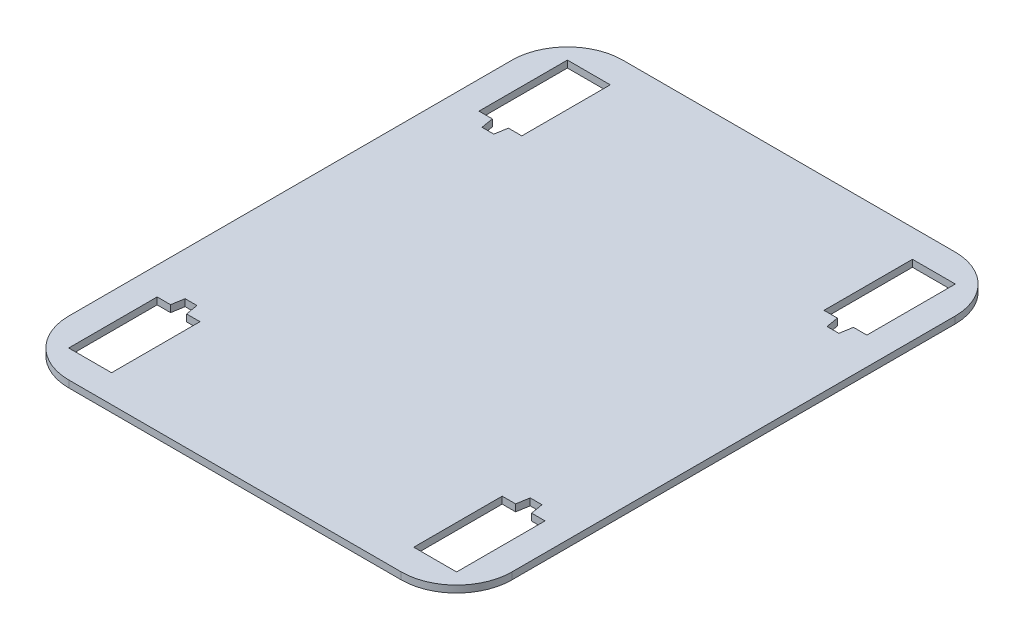
SolidWorks part; units mm, degrees
material "Plain Carbon Steel"
ref_plane "Front" through (0, 0, 0) normal (0, 0, 1) x (1, 0, 0)
ref_plane "Top" through (0, 0, 0) normal (0, 1, 0) x (1, 0, 0)
ref_plane "Right" through (0, 0, 0) normal (1, 0, 0) x (0, 0, -1)
sketch "Sketch1" plane through (0, 0, 0) normal (0, 1, 0) x (1, 0, 0)
  line L1 (-101.6, -127) -> (101.6, -127)
  line L2 (-101.6, -127) -> (-101.6, 127)
  line L3 (-101.6, 127) -> (101.6, 127)
  line L4 (101.6, -127) -> (101.6, 127)
  line L5 (-101.6, -127) -> (101.6, 127) construction
  line L6 (-101.6, 127) -> (101.6, -127) construction
  point P0 (0, 0)
  dimension "D1" = 254
  dimension "D2" = 203.2
extrude "Boss-Extrude1" add sketch "Sketch1" along normal blind 3.175
fillet "Fillet1" radius 25.4 4 edges at (-101.6, 1.5875, -127) (-101.6, 1.5875, 127) (101.6, 1.5875, -127) (101.6, 1.5875, 127)
sketch "Sketch2" plane through (0, 3.175, 0) normal (0, 1, 0) x (1, 0, 0)
  line L1 (-88.9254, 114.3254) -> (-69.2746, 114.3254)
  line L2 (-88.9254, 114.3254) -> (-88.9254, 73.7746)
  line L3 (-88.9254, 73.7746) -> (-69.2746, 73.7746)
  line L4 (-69.2746, 114.3254) -> (-69.2746, 73.7746)
  line L5 (-88.9254, 114.3254) -> (-69.2746, 73.7746) construction
  line L6 (-88.9254, 73.7746) -> (-69.2746, 114.3254) construction
  point P0 (-79.1, 94.05)
extrude "Cut-Extrude1" cut sketch "Sketch2" against normal through all
sketch "Sketch3" plane through (0, 0, 0) normal (0, -1, 0) x (1, 0, 0)
  line L0 (-82.7758, -73.7746) -> (-81.815, -68.0531)
  line L1 (-88.9254, -73.7746) -> (-69.2746, -73.7746) construction
  line L2 (-81.815, -68.0531) -> (-76.385, -68.0531)
  line L3 (-76.385, -68.0531) -> (-75.4242, -73.7746)
  line L4 (-75.4242, -73.7746) -> (-82.7758, -73.7746)
  line L5 (-82.7758, -73.7746) -> (-88.9254, -73.7746) construction
  line L6 (-75.4242, -73.7746) -> (-69.2746, -73.7746) construction
  point P4 (-76.1258, -67.8328)
  point P13 (-76.1287, -67.5062)
  point P14 (-75.0712, -73.7746)
  point P15 (-76.2485, -67.5062)
  point P16 (-75.4242, -73.7746)
  point P17 (-76.4768, -67.5062)
extrude "Cut-Extrude2" cut sketch "Sketch3" against normal through all
mirror "Mirror1" about plane through (0, 0, 0) normal (1, 0, 0) of "Cut-Extrude2", "Cut-Extrude1"
mirror "Mirror2" about plane through (0, 0, 0) normal (0, 0, 1) of "Mirror1", "Cut-Extrude2", "Cut-Extrude1"
